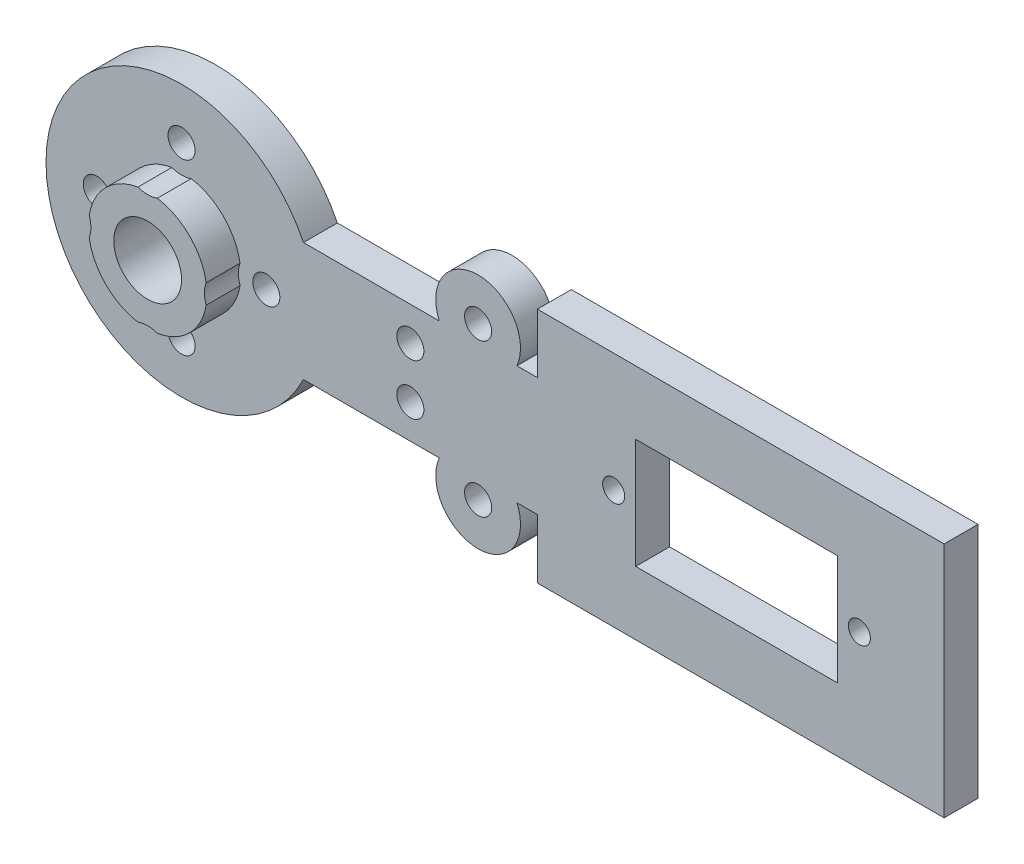
SolidWorks part; units mm, degrees
ref_plane "Front Plane" through (0, 0, 0) normal (0, 0, 1) x (1, 0, 0)
ref_plane "Top Plane" through (0, 0, 0) normal (0, 1, 0) x (1, 0, 0)
ref_plane "Right Plane" through (0, 0, 0) normal (1, 0, 0) x (0, 0, -1)
sketch "Main_web_profile" plane through (0, 0, 0) normal (0, 0, 1) x (1, 0, 0)
  line L1 (0, -7) -> (60, -7)
  line L2 (0, -7) -> (0, 7)
  line L3 (0, 7) -> (60, 7)
  line L4 (60, -7) -> (60, 7)
  dimension "D1" = 60
  dimension "D2" = 14
extrude "Main_web" add sketch "Main_web_profile" along normal blind 4
sketch "Shoulder_horn_flange_profile" plane through (0, 0, 0) normal (0, 0, 1) x (1, 0, 0)
  circle A0 centre (0, 0) radius 16
  dimension "D1" = 32
extrude "Shoulder_horn_flange" add sketch "Shoulder_horn_flange_profile" along normal blind 4
sketch "Elbow_servo_mount_profile" plane through (0, 0, 0) normal (0, 0, 1) x (1, 0, 0)
  line L1 (42, -14) -> (90, -14)
  line L2 (42, -14) -> (42, 14)
  line L3 (42, 14) -> (90, 14)
  line L4 (90, -14) -> (90, 14)
  dimension "D1" = 48
  dimension "D2" = 28
extrude "Elbow_servo_mount" add sketch "Elbow_servo_mount_profile" along normal blind 4
sketch "SG90_body_clearance_profile" plane through (0, 0, 0) normal (0, 0, 1) x (1, 0, 0)
  line L1 (53.6, -6.5) -> (77.4, -6.5)
  line L2 (53.6, -6.5) -> (53.6, 6.5)
  line L3 (53.6, 6.5) -> (77.4, 6.5)
  line L4 (77.4, -6.5) -> (77.4, 6.5)
  dimension "D1" = 23.8
  dimension "D2" = 13
extrude "SG90_body_clearance" cut sketch "SG90_body_clearance_profile" along normal through all from offset 5
sketch "Elbow_tab_fasteners_profile" plane through (0, 0, 0) normal (0, 0, 1) x (1, 0, 0)
  circle A0 centre (51, 0) radius 1.3
  circle A1 centre (80, 0) radius 1.3
  dimension "D1" = 2.6
  dimension "D2" = 2.6
extrude "Elbow_tab_fasteners" cut sketch "Elbow_tab_fasteners_profile" along normal through all from offset 50
sketch "Shoulder_center_screw_access_profile" plane through (0, 0, 0) normal (0, 0, 1) x (1, 0, 0)
  circle A0 centre (0, 0) radius 4
  dimension "D1" = 8
extrude "Shoulder_center_screw_access" cut sketch "Shoulder_center_screw_access_profile" along normal through all from offset 50
sketch "Shoulder_horn_bolt_pattern_profile" plane through (0, 0, 0) normal (0, 0, 1) x (1, 0, 0)
  circle A0 centre (0, 10) radius 1.6
  circle A1 centre (0, -10) radius 1.6
  circle A2 centre (10, 0) radius 1.6
  circle A3 centre (-10, 0) radius 1.6
  dimension "D1" = 3.2
  dimension "D2" = 3.2
  dimension "D3" = 3.2
  dimension "D4" = 3.2
extrude "Shoulder_horn_bolt_pattern" cut sketch "Shoulder_horn_bolt_pattern_profile" along normal through all from offset 50
sketch "Cable_tie_holes_profile" plane through (0, 0, 0) normal (0, 0, 1) x (1, 0, 0)
  circle A0 centre (27, -3) radius 1.6
  circle A1 centre (27, 3) radius 1.6
  dimension "D1" = 3.2
  dimension "D2" = 3.2
extrude "Cable_tie_holes" cut sketch "Cable_tie_holes_profile" along normal through all from offset 50
sketch "Passive_lower_mount_boss_profile" plane through (0, 0, 0) normal (0, 0, 1) x (1, 0, 0)
  circle A0 centre (35, -9) radius 5
  dimension "D1" = 10
extrude "Passive_lower_mount_boss" add sketch "Passive_lower_mount_boss_profile" along normal blind 4
sketch "Passive_upper_mount_boss_profile" plane through (0, 0, 0) normal (0, 0, 1) x (1, 0, 0)
  circle A0 centre (35, 9) radius 5
  dimension "D1" = 10
extrude "Passive_upper_mount_boss" add sketch "Passive_upper_mount_boss_profile" along normal blind 4
sketch "Passive_cheek_standoffs_profile" plane through (0, 0, 0) normal (0, 0, 1) x (1, 0, 0)
  circle A0 centre (35, -9) radius 1.6
  circle A1 centre (35, 9) radius 1.6
  dimension "D1" = 3.2
  dimension "D2" = 3.2
extrude "Passive_cheek_standoffs" cut sketch "Passive_cheek_standoffs_profile" along normal through all from offset 50
sketch "Shoulder_dowel_support_hub_profile" plane through (0, 0, 0) normal (0, 0, 1) x (1, 0, 0)
  circle A0 centre (0, 0) radius 7
  circle A1 centre (0, 0) radius 4
  dimension "D1" = 14
  dimension "D2" = 8
extrude "Shoulder_dowel_support_hub" add sketch "Shoulder_dowel_support_hub_profile" along normal blind 4 from offset 4
sketch "Shoulder_horn_washer_hub_relief_profile" plane through (0, 0, 0) normal (0, 0, 1) x (1, 0, 0)
  circle A0 centre (10, 0) radius 3.3
  circle A1 centre (-10, 0) radius 3.3
  circle A2 centre (0, 10) radius 3.3
  circle A3 centre (0, -10) radius 3.3
  dimension "D1" = 6.6
  dimension "D2" = 6.6
  dimension "D3" = 6.6
  dimension "D4" = 6.6
extrude "Shoulder_horn_washer_hub_relief" cut sketch "Shoulder_horn_washer_hub_relief_profile" along normal blind 4 from offset 4
